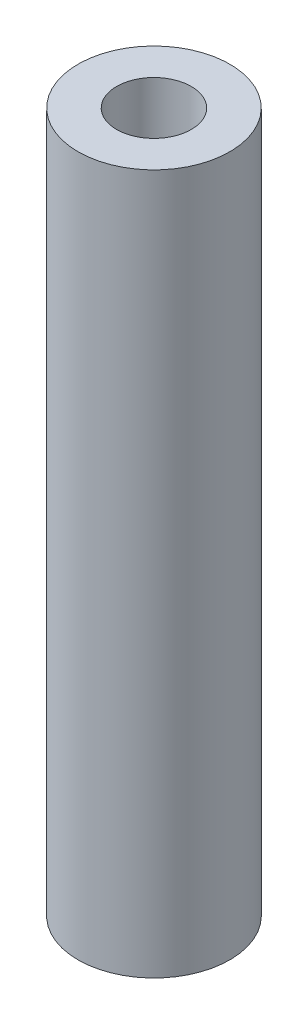
SolidWorks part; units mm, degrees
ref_plane "Front Plane" through (0, 0, 0) normal (0, 0, 1) x (1, 0, 0)
ref_plane "Top Plane" through (0, 0, 0) normal (0, 1, 0) x (1, 0, 0)
ref_plane "Right Plane" through (0, 0, 0) normal (1, 0, 0) x (0, 0, -1)
sketch "Sketch6" plane through (0, 0, 0) normal (0, 1, 0) x (1, 0, 0)
  circle A0 centre (0, 0) radius 4.1313
  dimension "D1" = 8.2625
extrude "Boss-Extrude4" add sketch "Sketch6" along normal blind 38.1
sketch "Sketch7" plane through (0, 38.1, 0) normal (0, 1, 0) x (1, 0, 0)
  circle A1 centre (0, 0) radius 2.032
  dimension "D1" = 4.064
extrude "Cut-Extrude2" cut sketch "Sketch7" against normal blind 38.1
